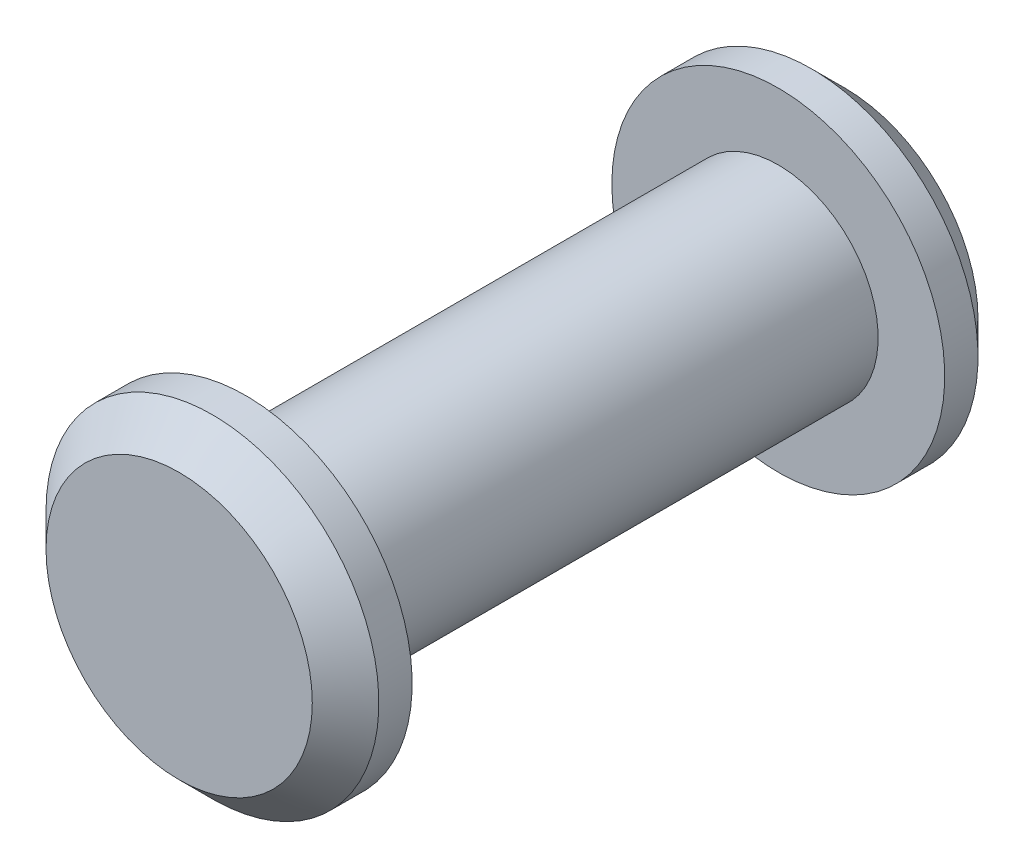
SolidWorks part; units mm, degrees
ref_plane "Front Plane" through (0, 0, 0) normal (0, 0, 1) x (1, 0, 0)
ref_plane "Top Plane" through (0, 0, 0) normal (0, 1, 0) x (1, 0, 0)
ref_plane "Right Plane" through (0, 0, 0) normal (1, 0, 0) x (0, 0, -1)
sketch "Sketch1" plane through (0, 0, 0) normal (0, 1, 0) x (1, 0, 0)
  line L0 (0, 20) -> (0, -20) construction
  line L1 (0, 20) -> (8, 20)
  line L2 (10, 18) -> (10, 16)
  line L3 (10, 16) -> (6, 16)
  line L5 (6, 16) -> (6, -16)
  line L6 (8, 20) -> (10, 18)
  line L7 (10, -16) -> (6, -16)
  line L8 (10, -18) -> (10, -16)
  line L9 (8, -20) -> (10, -18)
  line L10 (0, -20) -> (8, -20)
  line L11 (0, 20) -> (0, -20)
  point P3 (0, 0)
  point P5 (10, 20)
  dimension "D1" = 40
  dimension "D2" = 10
  dimension "D3" = 4
  dimension "D4" = 6
  dimension "D5" = 32
  dimension "D6" = 4
revolve "Revolve1" add sketch "Sketch1" angle 360 about L0
